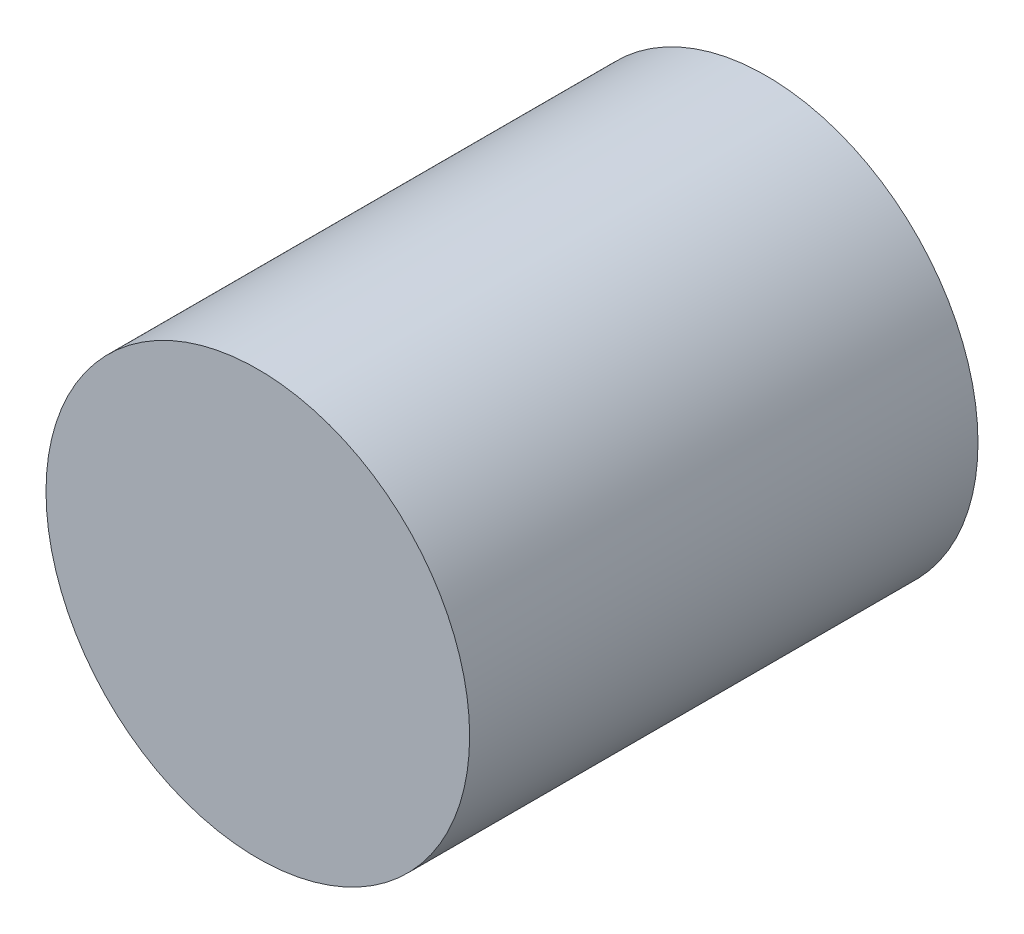
SolidWorks part; units mm, degrees
material "Plain Carbon Steel"
ref_plane "Front Plane" through (0, 0, 0) normal (0, 0, 1) x (1, 0, 0)
ref_plane "Top Plane" through (0, 0, 0) normal (0, 1, 0) x (1, 0, 0)
ref_plane "Right Plane" through (0, 0, 0) normal (1, 0, 0) x (0, 0, -1)
sketch "Sketch1" plane through (0, 0, 0) normal (0, 0, 1) x (1, 0, 0)
  circle A0 centre (0, 0) radius 31.75
  dimension "D1" = 63.5
extrude "Boss-Extrude1" add sketch "Sketch1" along normal blind 76.2
